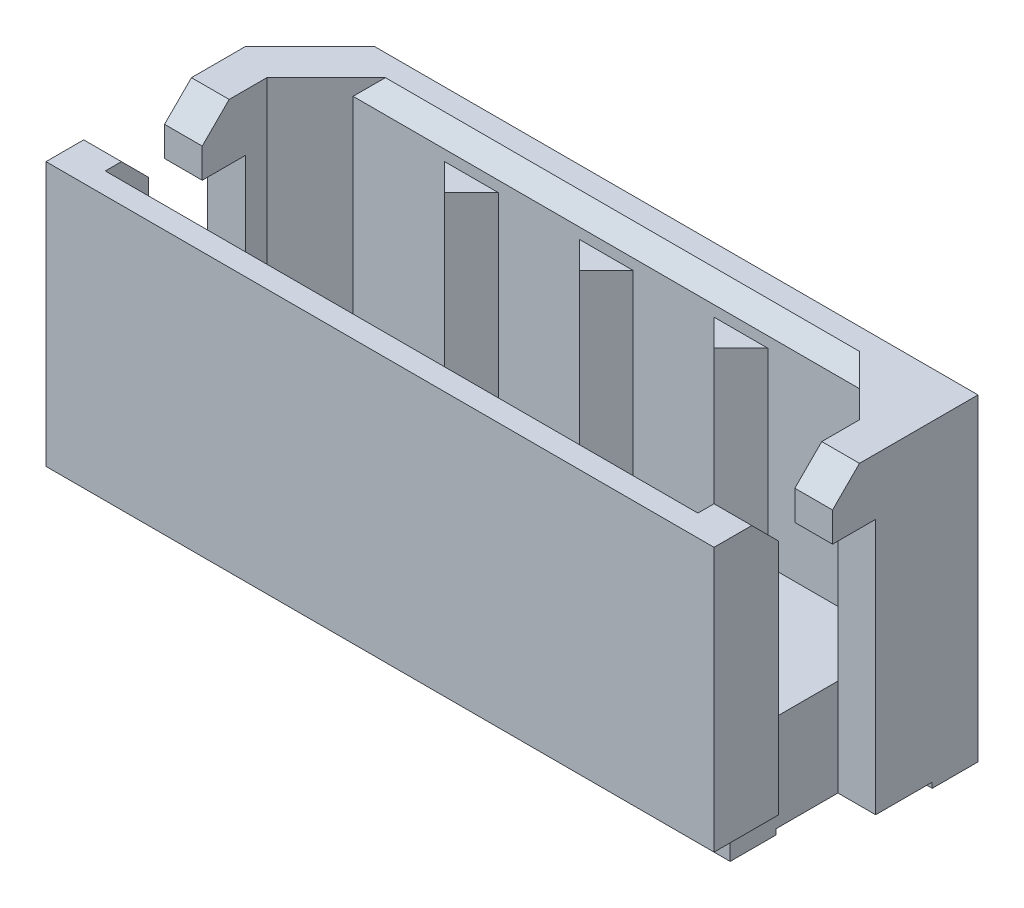
SolidWorks part; units mm, degrees
ref_plane "정면" through (0, 0, 0) normal (0, 0, 1) x (1, 0, 0)
ref_plane "윗면" through (0, 0, 0) normal (0, 1, 0) x (1, 0, 0)
ref_plane "우측면" through (0, 0, 0) normal (1, 0, 0) x (0, 0, -1)
sketch "스케치1" plane through (0, 0, 0) normal (0, 0, 1) x (1, 0, 0)
  line L1 (0, 0) -> (12.4, 0)
  line L2 (0, 0) -> (0, 5.9)
  line L3 (0, 5.9) -> (12.4, 5.9)
  line L4 (12.4, 0) -> (12.4, 5.9)
  dimension "D1" = 5.9
  dimension "D2" = 12.4
extrude "보스-돌출1" add sketch "스케치1" along normal blind 4.9
sketch "스케치2" plane through (0, 5.9, 0) normal (0, 1, 0) x (1, 0, 0)
  line L0 (12.4, -4.9) -> (0, -4.9) construction
  line L1 (12.4, 0) -> (0, 0) construction
  line L2 (12.4, -4.9) -> (12.4, 0) construction
  line L3 (0, -4.9) -> (0, 0) construction
  line L4 (12.4, -4.9) -> (0, -4.9) construction
  line L5 (12.4, 0) -> (0, 0) construction
  line L6 (12.4, -4.9) -> (12.4, 0) construction
  line L7 (0, -4.9) -> (0, 0) construction
  line L8 (11.7, -4.2) -> (0.7, -4.2) construction
  line L9 (0.7, -4.2) -> (0.7, -0.7) construction
  line L10 (11.7, -0.7) -> (0.7, -0.7) construction
  line L11 (11.7, -4.2) -> (11.7, -0.7) construction
  line L12 (0.7, -1.5) -> (1.5, -0.7)
  line L13 (10.9, -0.7) -> (11.7, -1.5)
  line L14 (0.7, -1.5) -> (0.7, -4.2)
  line L15 (0.7, -4.2) -> (11.7, -4.2)
  line L16 (11.7, -4.2) -> (11.7, -1.5)
  line L17 (1.5, -0.7) -> (10.9, -0.7)
  dimension "D2" = 45
  dimension "D3" = 45
  dimension "D4" = 0.8
  dimension "D5" = 0.8
  dimension "D1" = 0.7
extrude "컷-돌출1" cut sketch "스케치2" against normal offset from surface (4 mm away) 1.9 up to face at (6.2, 0, 2.45)
sketch "스케치4" plane through (12.4, 0, 0) normal (1, 0, 0) x (0, 0, -1)
  line L0 (-4.9, 0) -> (0, 0) construction
  line L1 (-4.9, 0) -> (-3.9, 0)
  line L2 (-4.9, 0) -> (-4.9, 1)
  line L3 (-4.9, 1) -> (-3.9, 1)
  line L4 (-3.9, 0) -> (-3.9, 1)
  line L5 (-0.85, 0) -> (-3.05, 0)
  line L6 (-0.85, 0) -> (-0.85, 0.1)
  line L7 (-0.85, 0.1) -> (-3.05, 0.1)
  line L8 (-3.05, 0) -> (-3.05, 0.1)
  line L9 (-3.7, 5.4) -> (-4.2, 5.9)
  line L10 (-3.7, 1.9) -> (-1.9, 1.9)
  line L11 (-3.7, 1.9) -> (-3.7, 5.4)
  line L12 (-4.9, 5.9) -> (0, 5.9) construction
  line L13 (-1.9, 1.9) -> (-1.9, 4.85)
  line L14 (-1.9, 4.85) -> (-2.7, 4.85)
  line L15 (-2.7, 4.85) -> (-2.7, 5.4)
  line L16 (-2.7, 5.4) -> (-2.2, 5.9)
  line L18 (-1.5, 1.9) -> (-4.2, 1.9) construction
  line L19 (-4.9, 0) -> (-4.9, 5.9) construction
  line L20 (-4.2, 5.9) -> (-2.2, 5.9)
  line L21 (-1.5, 1.9) -> (-4.2, 1.9) construction
  dimension "D1" = 1
  dimension "D2" = 1
  dimension "D3" = 0.1
  dimension "D4" = 0.85
  dimension "D5" = 0.85
  dimension "D6" = 45
  dimension "D7" = 45
  dimension "D8" = 1
  dimension "D9" = 1.2
  dimension "D10" = 2
  dimension "D11" = 0.55
extrude "컷-돌출2" cut sketch "스케치4" against normal through all
sketch "스케치5" plane through (0, 0, 3.9) normal (0, 0, 1) x (1, 0, 0)
  line L0 (0, 1) -> (12.4, 1) construction
  line L1 (0, 0) -> (0.7, 0)
  line L2 (0, 0) -> (0, 1)
  line L3 (0, 1) -> (0.7, 1)
  line L4 (0.7, 0) -> (0.7, 1)
  line L5 (0, 0) -> (12.4, 0) construction
  line L6 (11.7, 0) -> (12.4, 0)
  line L7 (11.7, 0) -> (11.7, 1)
  line L8 (11.7, 1) -> (12.4, 1)
  line L9 (12.4, 0) -> (12.4, 1)
  line L13 (11.7, 1.9) -> (11.7, 5.9) construction
  line L14 (0.7, 1.9) -> (0.7, 5.9) construction
extrude "컷-돌출3" cut sketch "스케치5" against normal up to surface (2 mm away) up to face at (0.35, 3.375, 1.9)
chamfer "모따기1" distance 1.2 1 edges at (0, 2.95, 0)
sketch "스케치6" plane through (0, 0.1, 0) normal (0, -1, 0) x (1, 0, 0)
  line L0 (0.7, 3.05) -> (0.7, 1.9) construction
  line L2 (11.7, 4.2) -> (0.7, 4.2) construction
  circle A0 centre (2.45, 1.82) radius 0.35
  dimension "D1" = 0.7
  dimension "D2" = 1.75
  dimension "D3" = 2.38
extrude "컷-돌출4" cut sketch "스케치6" against normal through all
pattern_linear "선형 패턴1" count 4 spacing 2.5 along (1, 0, 0) of "컷-돌출4"
sketch "스케치7" plane through (0, 1, 0) normal (0, -1, 0) x (1, 0, 0)
  line L0 (0, 1.9) -> (0, 4.9) construction
  line L1 (0.7, 1.9) -> (0, 1.9)
  line L2 (0.7, 1.9) -> (0.7, 3.7)
  line L3 (0.7, 3.7) -> (0, 3.7)
  line L4 (0, 1.9) -> (0, 3.7)
  line L5 (12.4, 1.9) -> (12.4, 4.9) construction
  line L6 (11.7, 1.9) -> (12.4, 1.9)
  line L7 (11.7, 1.9) -> (11.7, 3.7)
  line L8 (11.7, 3.7) -> (12.4, 3.7)
  line L9 (12.4, 1.9) -> (12.4, 3.7)
extrude "컷-돌출5" cut sketch "스케치7" against normal up to next
sketch "스케치8" plane through (0, 1.9, 0) normal (0, 1, 0) x (1, 0, 0)
  line L0 (3.2, -0.7) -> (4.2, -0.7)
  line L1 (1.5, -0.7) -> (10.9, -0.7) construction
  line L2 (4.2, -0.7) -> (3.7, -1.2)
  line L3 (3.7, -1.2) -> (3.2, -0.7)
  circle A0 centre (2.45, -1.82) radius 0.35 construction
  circle A1 centre (2.45, -1.82) radius 0.35 construction
  dimension "D1" = 1.25
  dimension "D2" = 45
  dimension "D3" = 45
  dimension "D4" = 0.5
extrude "보스-돌출2" add sketch "스케치8" along normal blind 3.5
pattern_linear "선형 패턴2" count 3 spacing 2.5 along (1, 0, 0) of "보스-돌출2"
chamfer "모따기2" distance 0.3 angle 45 2 edges at (6.2, 5.9, 0.7) (6.2, 5.9, 4.2)
equation "\"D5@스케치2\"=\"D4@스케치2\""
